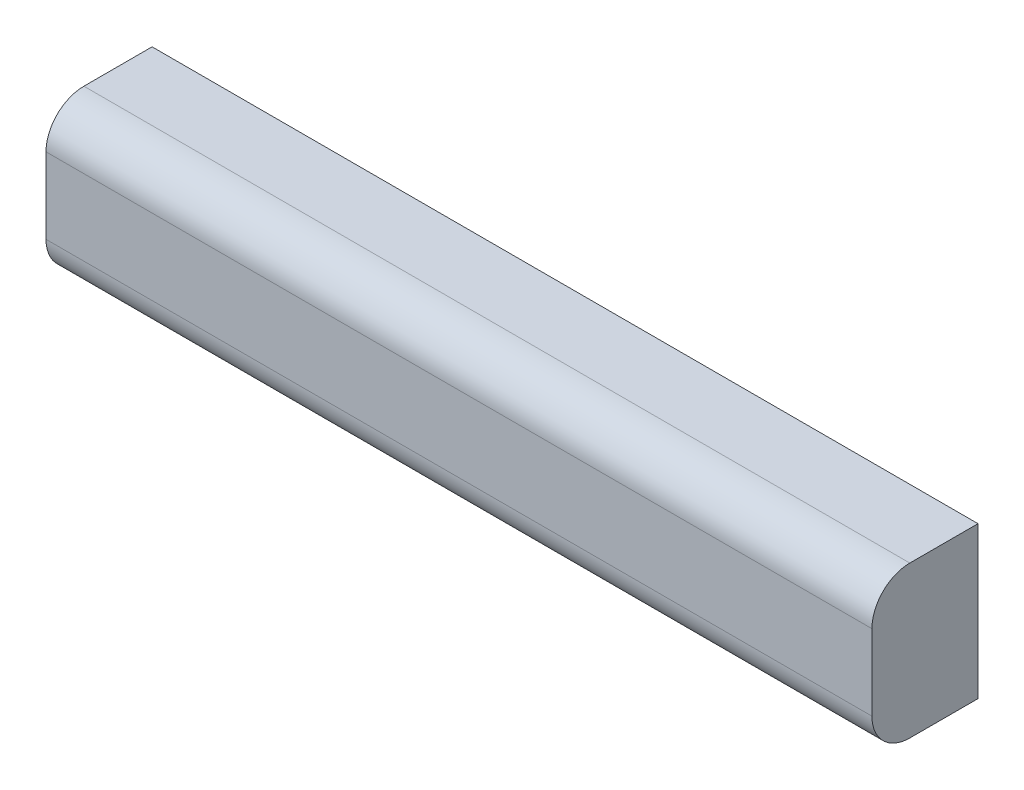
SolidWorks part; units mm, degrees
ref_plane "Front Plane" through (0, 0, 0) normal (0, 0, 1) x (1, 0, 0)
ref_plane "Top Plane" through (0, 0, 0) normal (0, 1, 0) x (1, 0, 0)
ref_plane "Right Plane" through (0, 0, 0) normal (1, 0, 0) x (0, 0, -1)
sketch "Sketch1" plane through (0, 0, 0) normal (0, 0, 1) x (1, 0, 0)
  line L1 (-346.075, 63.5) -> (346.075, 63.5)
  line L2 (-346.075, 63.5) -> (-346.075, -63.5)
  line L3 (-346.075, -63.5) -> (346.075, -63.5)
  line L4 (346.075, 63.5) -> (346.075, -63.5)
  line L5 (-346.075, 63.5) -> (346.075, -63.5) construction
  line L6 (-346.075, -63.5) -> (346.075, 63.5) construction
  point P0 (0, 0)
  dimension "D1" = 127
  dimension "D2" = 692.15
extrude "Boss-Extrude1" add sketch "Sketch1" along normal mid plane 88.9
fillet "Fillet1" radius 31.75 2 edges at (0, -63.5, 44.45) (0, 63.5, 44.45)
sketch "Sketch2" plane through (0, 0, -44.45) normal (0, 0, -1) x (-1, 0, 0)
  line L2 (0, -33.0793) -> (0, 33.0793) construction
  line L3 (-12.7, 0) -> (12.7, 0) construction
  line L4 (-183.3679, 0) -> (-157.9679, 0) construction
  circle A0 centre (157.9679, 0) radius 4.7625
  circle A1 centre (183.3679, 0) radius 4.7625
  circle A2 centre (12.7, 0) radius 4.7625
  circle A3 centre (-12.7, 0) radius 4.7625
  circle A4 centre (-157.9679, 0) radius 4.7625
  circle A5 centre (-183.3679, 0) radius 4.7625
  point P6 (0, 0)
  point P9 (0, 0)
  point P15 (0, 0)
  point P20 (-170.6679, 0)
  dimension "D1" = 25.4
  dimension "D2" = 9.525
  dimension "D3" = 9.525
  dimension "D4" = 25.4
extrude "Cut-Extrude1" cut sketch "Sketch2" against normal blind 25.4
